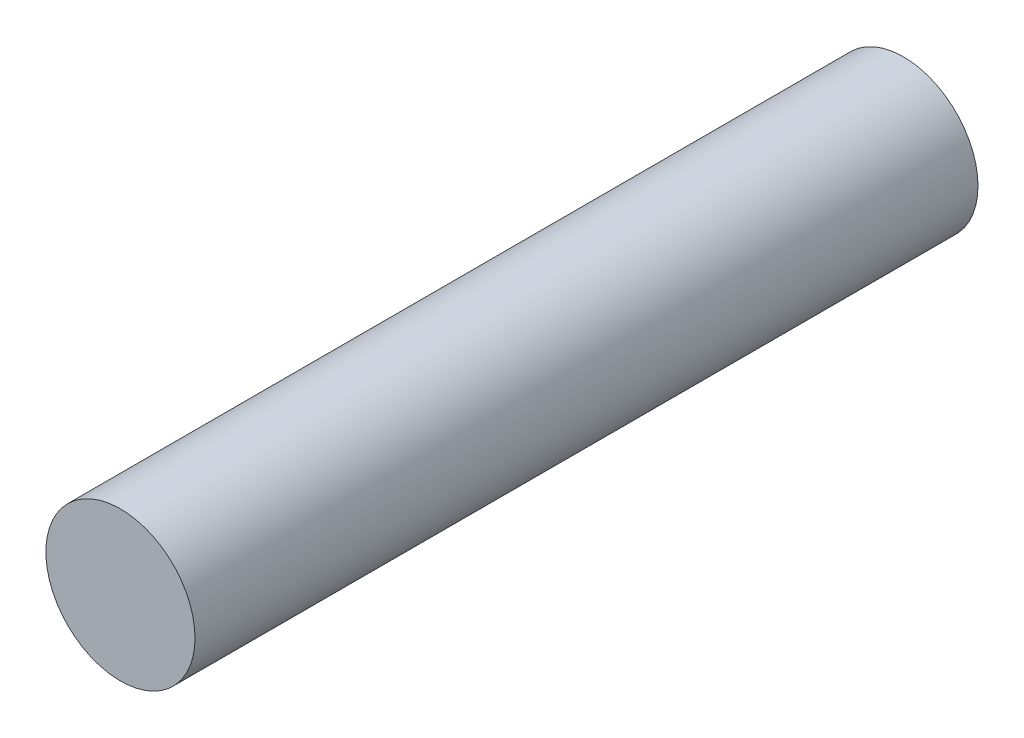
SolidWorks part; units mm, degrees
material "1060 Alloy"
ref_plane "Front Plane" through (0, 0, 0) normal (0, 0, 1) x (1, 0, 0)
ref_plane "Top Plane" through (0, 0, 0) normal (0, 1, 0) x (1, 0, 0)
ref_plane "Right Plane" through (0, 0, 0) normal (1, 0, 0) x (0, 0, -1)
sketch "Sketch2" plane through (0, 0, 0) normal (0, 0, 1) x (1, 0, 0)
  circle A0 centre (0, 0) radius 12.7
  dimension "D1" = 25.4
extrude "Boss-Extrude1" add sketch "Sketch2" along normal blind 133.35
